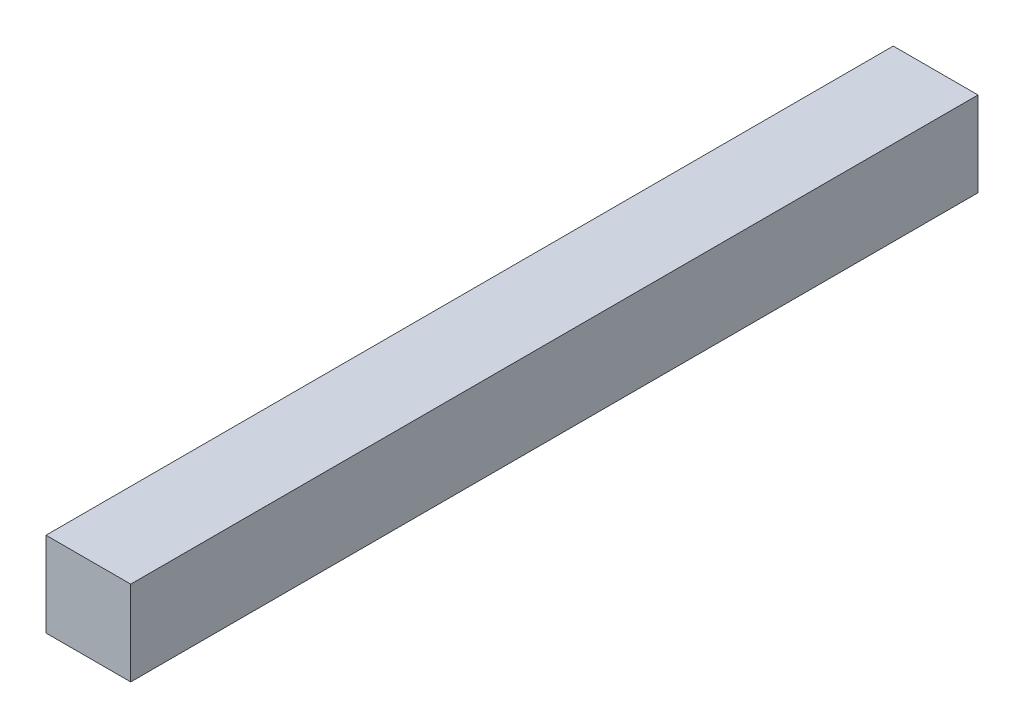
SolidWorks part; units mm, degrees
ref_plane "Front Plane" through (0, 0, 0) normal (0, 0, 1) x (1, 0, 0)
ref_plane "Top Plane" through (0, 0, 0) normal (0, 1, 0) x (1, 0, 0)
ref_plane "Right Plane" through (0, 0, 0) normal (1, 0, 0) x (0, 0, -1)
sketch "Sketch1" plane through (0, 0, 0) normal (0, 0, 1) x (1, 0, 0)
  line L1 (-5, 5) -> (5, 5)
  line L2 (-5, 5) -> (-5, -5)
  line L3 (-5, -5) -> (5, -5)
  line L4 (5, 5) -> (5, -5)
  dimension "D1" = 10
  dimension "D2" = 10
  dimension "D3" = 5
  dimension "D4" = 5
extrude "Boss-Extrude1" add sketch "Sketch1" along normal blind 100
